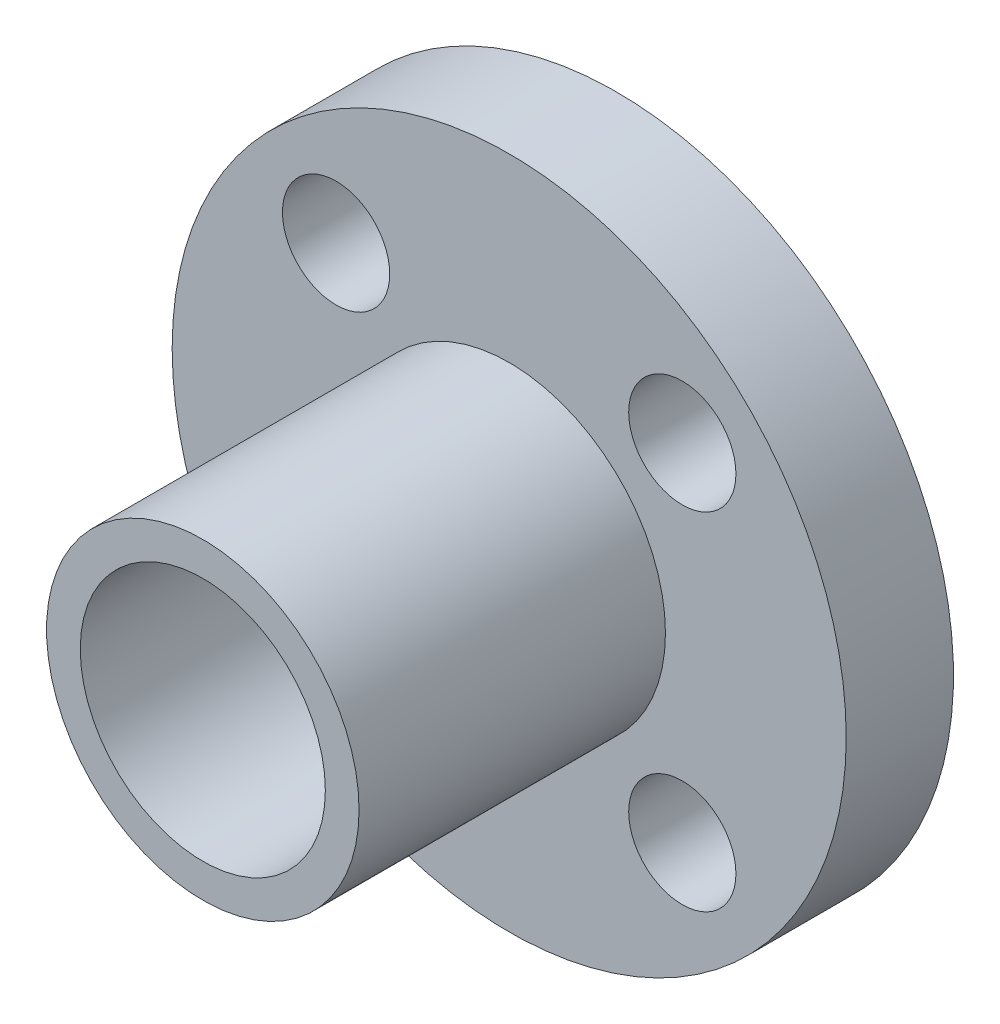
SolidWorks part; units mm, degrees
ref_plane "Ön Düzlem" through (0, 0, 0) normal (0, 0, 1) x (1, 0, 0)
ref_plane "Üst Düzlem" through (0, 0, 0) normal (0, 1, 0) x (1, 0, 0)
ref_plane "Sağ Düzlem" through (0, 0, 0) normal (1, 0, 0) x (0, 0, -1)
sketch "Sketch1" plane through (0, 0, 0) normal (0, 0, 1) x (1, 0, 0)
  circle A0 centre (0, 0) radius 11
  dimension "D1" = 22
extrude "Boss-Extrude1" add sketch "Sketch1" along normal blind 15
sketch "Sketch2" plane through (0, 0, 15) normal (0, 0, 1) x (1, 0, 0)
  circle A0 centre (0, 0) radius 5.1
  dimension "D1" = 10.2
extrude "Cut-Extrude1" cut sketch "Sketch2" against normal blind 10 flip side to cut
sketch "Sketch3" plane through (0, 0, 0) normal (0, 0, -1) x (-1, 0, 0)
  circle A0 centre (0, 0) radius 5.1
  dimension "D1" = 10.2
extrude "Cut-Extrude2" cut sketch "Sketch3" against normal blind 1.5 flip side to cut
sketch "Sketch8" plane through (0, 0, 1.5) normal (0, 0, -1) x (-1, 0, 0)
  line L1 (-5.65, 5.65) -> (5.65, 5.65) construction
  line L2 (-5.65, 5.65) -> (-5.65, -5.65) construction
  line L3 (-5.65, -5.65) -> (5.65, -5.65) construction
  line L4 (5.65, 5.65) -> (5.65, -5.65) construction
  line L5 (-5.65, 5.65) -> (5.65, -5.65) construction
  line L6 (-5.65, -5.65) -> (5.65, 5.65) construction
  circle A0 centre (-5.65, -5.65) radius 1.75
  circle A1 centre (-5.65, 5.65) radius 1.75
  circle A2 centre (5.65, 5.65) radius 1.75
  circle A3 centre (5.65, -5.65) radius 1.75
  point P0 (0, 0)
  dimension "D1" = 3.5
  dimension "D2" = 11.3
  dimension "D3" = 11.3
extrude "Cut-Extrude3" cut sketch "Sketch8" against normal through all
sketch "Sketch9" plane through (0, 0, 0) normal (0, 0, -1) x (-1, 0, 0)
  circle A0 centre (0, 0) radius 4
  dimension "D1" = 8
extrude "Cut-Extrude4" cut sketch "Sketch9" against normal through all
